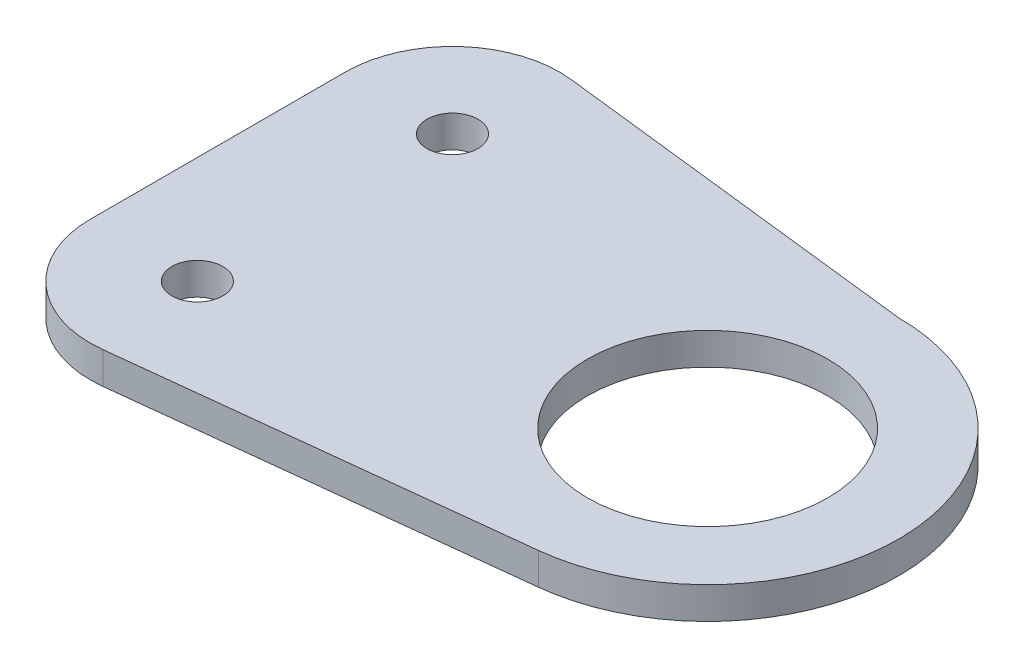
SolidWorks part; units mm, degrees
ref_plane "Front Plane" through (0, 0, 0) normal (0, 0, 1) x (1, 0, 0)
ref_plane "Top Plane" through (0, 0, 0) normal (0, 1, 0) x (1, 0, 0)
ref_plane "Right Plane" through (0, 0, 0) normal (1, 0, 0) x (0, 0, -1)
sketch "Sketch1" plane through (0, 0, 0) normal (0, 1, 0) x (1, 0, 0)
  line L3 (0, 0) -> (-1.4483, 0.4828) construction
  line L4 (-48.768, 12.7) -> (-48.768, -12.7)
  line L5 (-36.913, -23.3018) -> (2.1196, -18.9317)
  line L6 (-36.8793, 23.2979) -> (0, 19.05)
  line L8 (-1.4483, 0.4828) -> (0, 0) construction
  circle A0 centre (0, 0) radius 11.9697
  circle A1 centre (-38.1, 12.7) radius 2.54
  circle A2 centre (-38.1, -12.7) radius 2.54
  arc A3 (-36.8793, 23.2979) -> (-48.768, 12.7) centre (-38.1, 12.7) ccw
  arc A4 (-48.768, -12.7) -> (-36.913, -23.3018) centre (-38.1, -12.7) ccw
  arc A5 (2.1196, -18.9317) -> (0, 19.05) centre (0, 0) ccw
  point P13 (19.0204, 1.0614)
  dimension "D1" = 23.9395
  dimension "D4" = 5.08
  dimension "D5" = 21.336
  dimension "D6" = 38.1
  dimension "D2" = 46.5997
  dimension "D3" = 25.4
  dimension "D7" = 67.7884
extrude "Boss-Extrude1" add sketch "Sketch1" along normal blind 3.175
sketch "Sketch2" plane through (0, 0, 0) normal (0, -1, 0) x (1, 0, 0)
  line L0 (-48.768, -2.5631) -> (-48.768, -12.7)
  line L3 (-36.8793, -23.2979) -> (0, -19.05)
  line L4 (2.1196, 18.9317) -> (-36.913, 23.3018)
  line L5 (-48.768, 12.7) -> (-48.768, -12.7)
  line L6 (-36.8793, -23.2979) -> (0, -19.05)
  line L7 (2.1196, 18.9317) -> (-36.913, 23.3018)
  line L8 (-48.768, 12.7) -> (-48.768, 2.5631)
  arc A0 (18.9137, 2.2746) -> (2.1196, 18.9317) centre (0, 0) ccw
  arc A3 (-48.768, -12.7) -> (-36.8793, -23.2979) centre (-38.1, -12.7) ccw
  arc A4 (0, -19.05) -> (2.1196, 18.9317) centre (0, 0) ccw
  arc A5 (-36.913, 23.3018) -> (-48.768, 12.7) centre (-38.1, 12.7) ccw
  arc A6 (-48.768, -12.7) -> (-36.8793, -23.2979) centre (-38.1, -12.7) ccw
  arc A7 (0, -19.05) -> (18.9137, -2.2746) centre (0, 0) ccw
  arc A8 (-36.913, 23.3018) -> (-48.768, 12.7) centre (-38.1, 12.7) ccw
  dimension "D1" = 0
